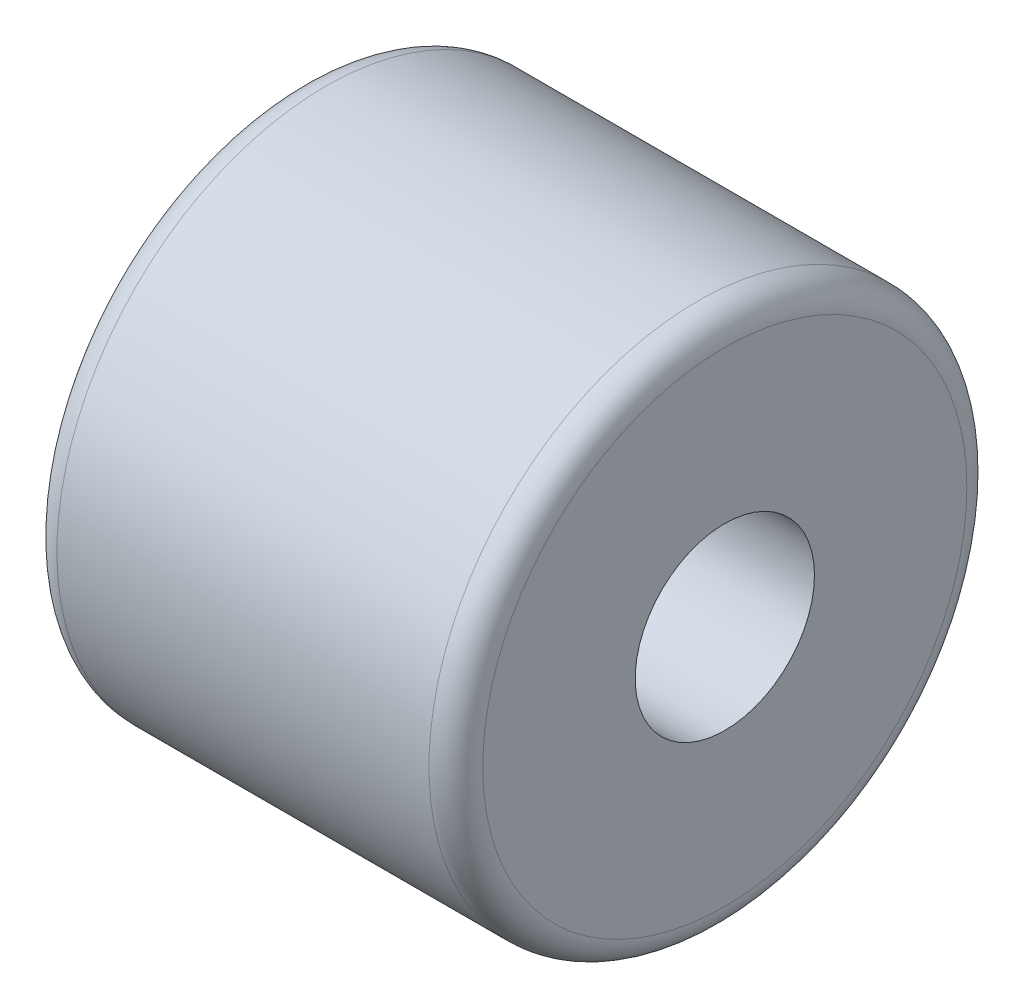
SolidWorks part; units mm, degrees
ref_plane "Plan de face" through (0, 0, 0) normal (0, 0, 1) x (1, 0, 0)
ref_plane "Plan de dessus" through (0, 0, 0) normal (0, 1, 0) x (1, 0, 0)
ref_plane "Plan de droite" through (0, 0, 0) normal (1, 0, 0) x (0, 0, -1)
sketch "Esquisse1" plane through (0, 0, 0) normal (1, 0, 0) x (0, 0, -1)
  circle A0 centre (0, 0) radius 6
  circle A1 centre (0, 0) radius 2
  dimension "D1" = 4
  dimension "D2" = 4
extrude "Boss.-Extru.1" add sketch "Esquisse1" along normal mid plane 9.5
fillet "Congé1" radius 0.6 2 edges at (4.75, 0, -6) (-4.75, 0, -6)
